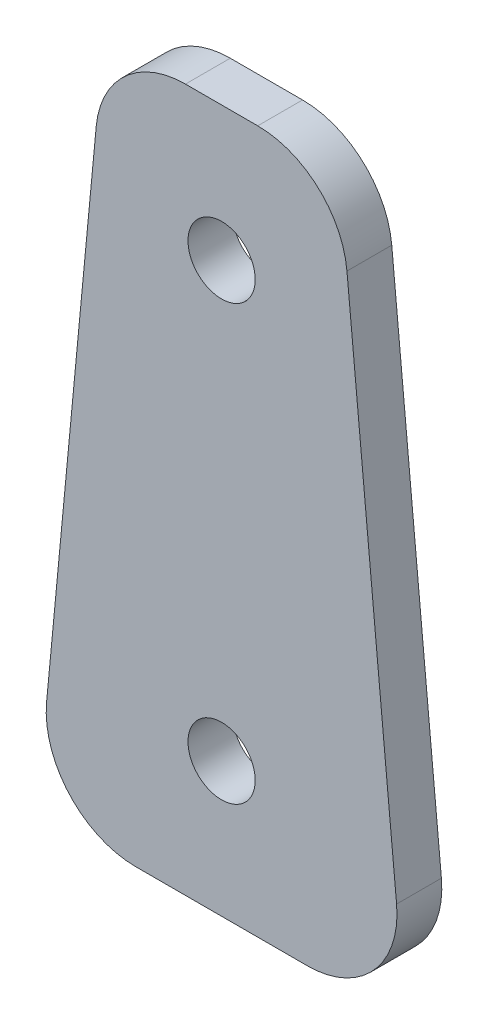
SolidWorks part; units mm, degrees
ref_plane "Front Plane" through (0, 0, 0) normal (0, 0, 1) x (1, 0, 0)
ref_plane "Top Plane" through (0, 0, 0) normal (0, 1, 0) x (1, 0, 0)
ref_plane "Right Plane" through (0, 0, 0) normal (1, 0, 0) x (0, 0, -1)
sketch "Sketch1" plane through (0, 0, 0) normal (0, 0, 1) x (1, 0, 0)
  line L1 (36.2115, 120.3605) -> (32.6949, 157.4445)
  line L3 (14.9301, 157.4445) -> (11.4135, 120.3605)
  line L4 (29.8899, 113.411) -> (17.7351, 113.411)
  line L5 (21.2517, 163.195) -> (26.3733, 163.195)
  arc A0 (21.2517, 163.195) -> (14.9301, 157.4445) centre (21.2517, 156.845) ccw
  arc A1 (26.3733, 163.195) -> (32.6949, 157.4445) centre (26.3733, 156.845) cw
  arc A2 (29.8899, 113.411) -> (36.2115, 120.3605) centre (29.8899, 119.761) ccw
  circle A3 centre (23.8125, 122.936) radius 2.3813
  circle A4 centre (23.8125, 153.67) radius 2.3813
  arc A7 (17.7351, 113.411) -> (11.4135, 120.3605) centre (17.7351, 119.761) cw
  dimension "D1" = 6.35
  dimension "D7" = 9.525
  dimension "D8" = 9.525
extrude "Boss-Extrude1" add sketch "Sketch1" along normal blind 3.175
